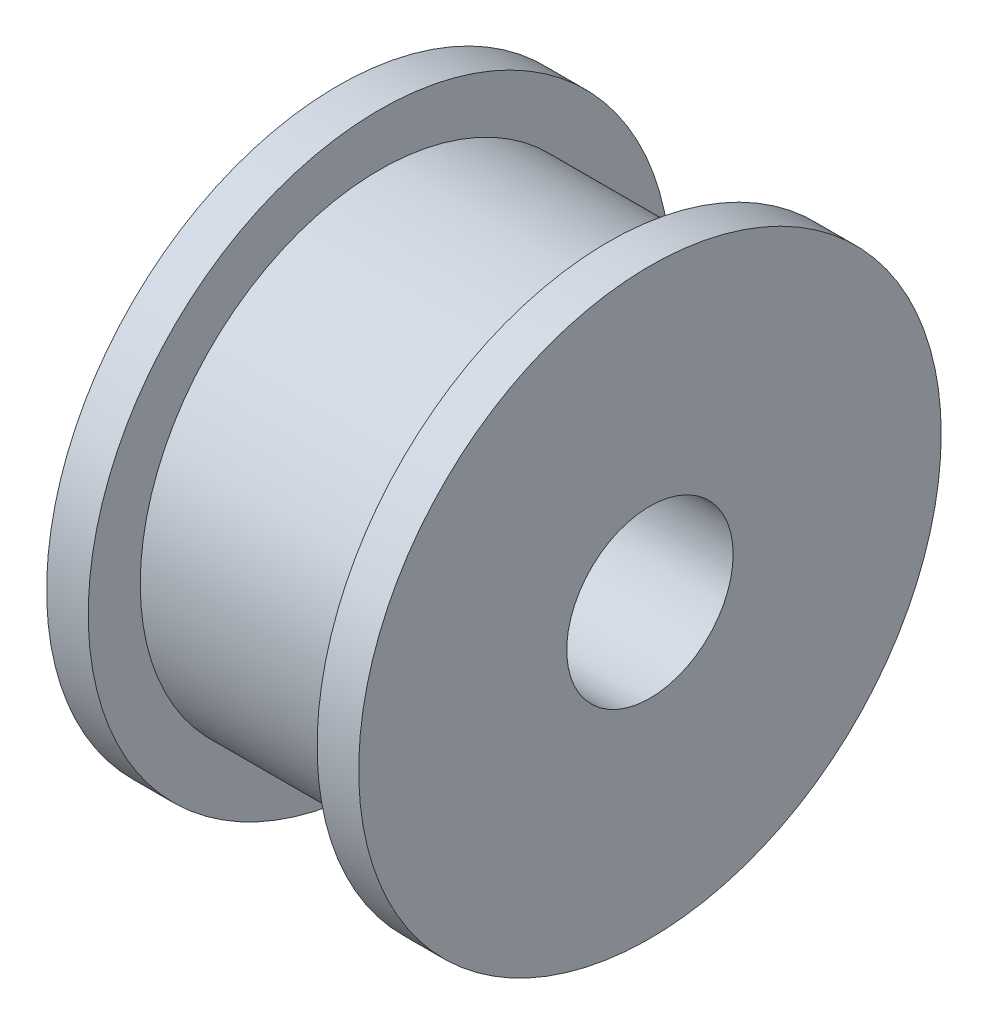
SolidWorks part; units mm, degrees
ref_plane "前视基准面" through (0, 0, 0) normal (0, 0, 1) x (1, 0, 0)
ref_plane "上视基准面" through (0, 0, 0) normal (0, 1, 0) x (1, 0, 0)
ref_plane "右视基准面" through (0, 0, 0) normal (1, 0, 0) x (0, 0, -1)
sketch "Sketch1" plane through (0, 0, 0) normal (1, 0, 0) x (0, 0, -1)
  circle A0 centre (0, 0) radius 14
  circle A1 centre (0, 0) radius 4
  dimension "D1" = 28
  dimension "D2" = 8
extrude "Boss-Extrude1" add sketch "Sketch1" along normal mid plane 15
sketch "Sketch2" plane through (0, 0, 0) normal (1, 0, 0) x (0, 0, -1)
  circle A0 centre (0, 0) radius 11.5
  dimension "D1" = 23
extrude "Cut-Extrude1" cut sketch "Sketch2" against normal mid plane 11 flip side to cut
